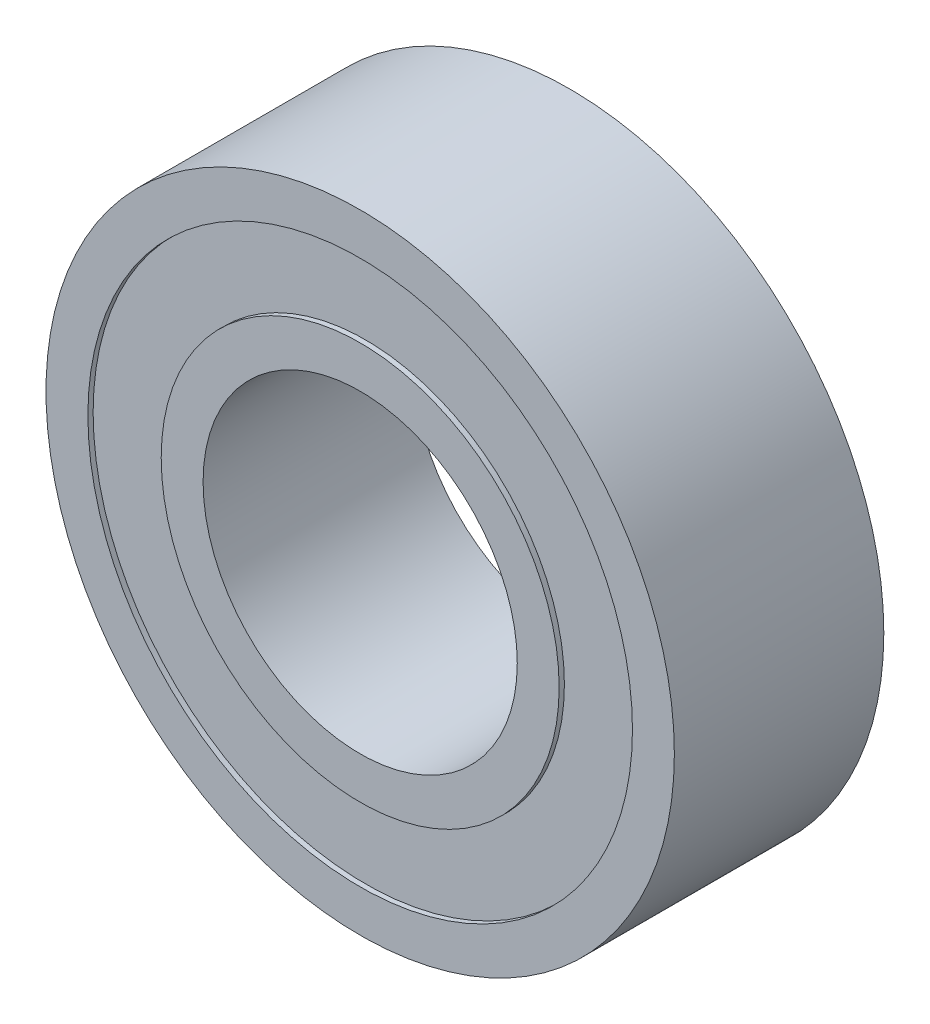
SolidWorks part; units mm, degrees
ref_plane "Front Plane" through (0, 0, 0) normal (0, 0, 1) x (1, 0, 0)
ref_plane "Top Plane" through (0, 0, 0) normal (0, 1, 0) x (1, 0, 0)
ref_plane "Right Plane" through (0, 0, 0) normal (1, 0, 0) x (0, 0, -1)
sketch "Sketch1" plane through (0, 0, 0) normal (0, 0, 1) x (1, 0, 0)
  circle A0 centre (0, 0) radius 6
  circle A1 centre (0, 0) radius 3
  dimension "D1" = 12
  dimension "D2" = 6
extrude "Boss-Extrude1" add sketch "Sketch1" along normal mid plane 4
sketch "Sketch2" plane through (0, 0, 2) normal (0, 0, 1) x (1, 0, 0)
  circle A2 centre (0, 0) radius 5.2
  circle A3 centre (0, 0) radius 5.2
  circle A5 centre (0, 0) radius 3.8
  circle A6 centre (0, 0) radius 3.8
  dimension "D1" = 0.8
  dimension "D2" = 0.8
extrude "Cut-Extrude1" cut sketch "Sketch2" against normal blind 0.1
mirror "Mirror1" about plane through (0, 0, 0) normal (0, 0, 1) of "Cut-Extrude1"
